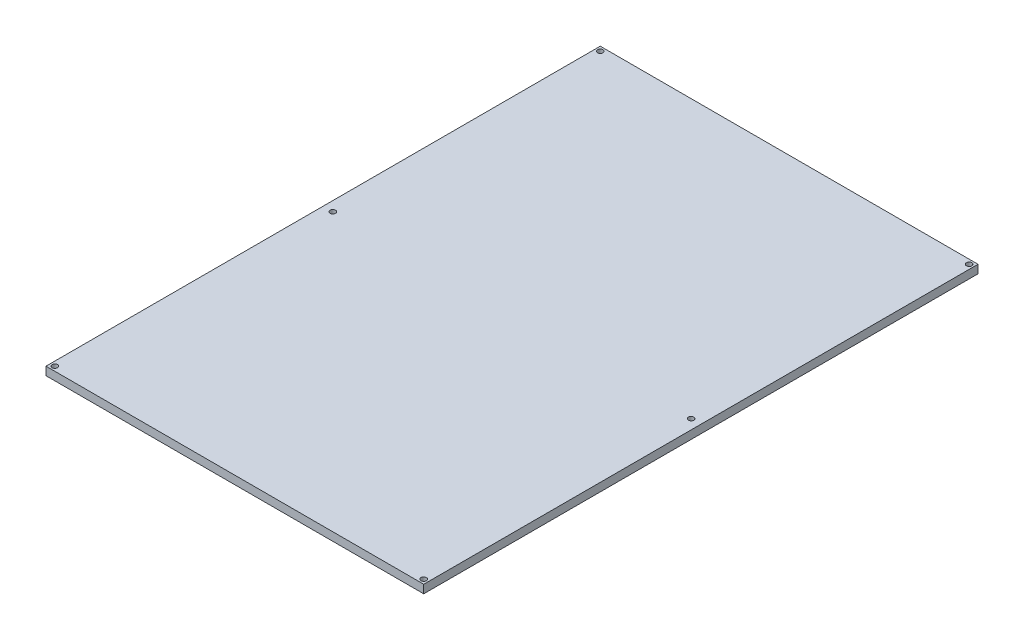
SolidWorks part; units mm, degrees
ref_plane "Alzado" through (0, 0, 0) normal (0, 0, 1) x (1, 0, 0)
ref_plane "Planta" through (0, 0, 0) normal (0, 1, 0) x (1, 0, 0)
ref_plane "Vista lateral" through (0, 0, 0) normal (1, 0, 0) x (0, 0, -1)
sketch "Croquis1" plane through (0, 0, 0) normal (0, 1, 0) x (1, 0, 0)
  line L0 (107, 314) -> (107, 0) construction
  line L1 (0, 0) -> (214, 0)
  line L2 (0, 0) -> (0, 314)
  line L3 (0, 314) -> (214, 314)
  line L4 (214, 0) -> (214, 314)
  line L5 (0, 157) -> (214, 157) construction
  circle A0 centre (2.5, 311.5) radius 1.55
  circle A1 centre (211.5, 311.5) radius 1.55
  circle A2 centre (2.5, 2.5) radius 1.55
  circle A3 centre (211.5, 2.5) radius 1.55
  circle A4 centre (5.5, 157) radius 1.55
  circle A5 centre (208.5, 157) radius 1.55
  dimension "D5" = 3.1
  dimension "D6" = 5.5
  dimension "D1" = 214
  dimension "D2" = 314
  dimension "D3" = 2.5
  dimension "D4" = 2.5
extrude "Saliente-Extruir1" add sketch "Croquis1" along normal blind 4.7
